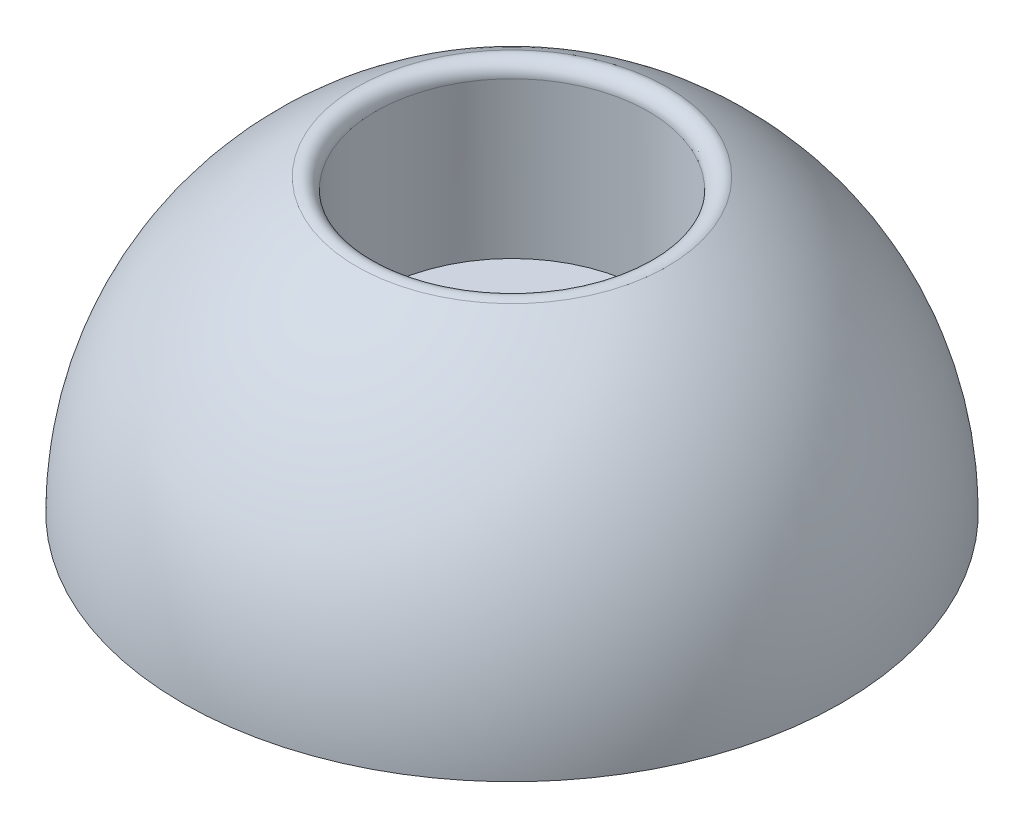
SolidWorks part; units mm, degrees
ref_plane "Front Plane" through (0, 0, 0) normal (0, 0, 1) x (1, 0, 0)
ref_plane "Top Plane" through (0, 0, 0) normal (0, 1, 0) x (1, 0, 0)
ref_plane "Right Plane" through (0, 0, 0) normal (1, 0, 0) x (0, 0, -1)
sketch "Sketch2" plane through (0, 0, 0) normal (0, 0, 1) x (1, 0, 0)
  line L0 (0, 0) -> (0, 12.7)
  line L1 (0, 0) -> (12.7, 0)
  arc A0 (12.7, 0) -> (0, 12.7) centre (0, 0) ccw
  dimension "D1" = 12.7
revolve "Revolve1" add sketch "Sketch2" angle 360 about L0
hole_wizard "M6 Clearance Hole1" positions "Sketch4" profile "Sketch5" hole size "M6" standard "ANSI Metric" end condition through all
sketch "Sketch4" plane through (0, 0, 0) normal (0, -1, 0) x (-1, 0, 0)
  point P0 (0, 0)
sketch "Sketch5" plane through (0, 0, 0) normal (1, 0, 0) x (0, 0, -1)
  line L0 (0, 0) -> (0, 12.7)
  line L1 (0, 12.7) -> (3.3, 12.7)
  line L2 (3.3, 12.7) -> (3.3, 0)
  line L5 (3.3, 0) -> (0, 0)
  line L11 (0, -6.35) -> (0, 107.95) construction
  dimension "Thru Hole Dia." = 6.6
  dimension "Thru Hole Depth" = 12.7
ref_plane "Plane1" through (0, 12.2638, 0) normal (0, 1, 0) x (1, 0, 0)
sketch "Sketch6" plane through (0, 12.2638, 0) normal (0, 1, 0) x (1, 0, 0)
  circle A0 centre (0, 0) radius 5.25
  dimension "D1" = 10.5
extrude "Cut-Extrude1" cut sketch "Sketch6" against normal blind 7.5
fillet "Fillet1" radius 0.5 1 edges at (0, 11.5641, -5.25)
